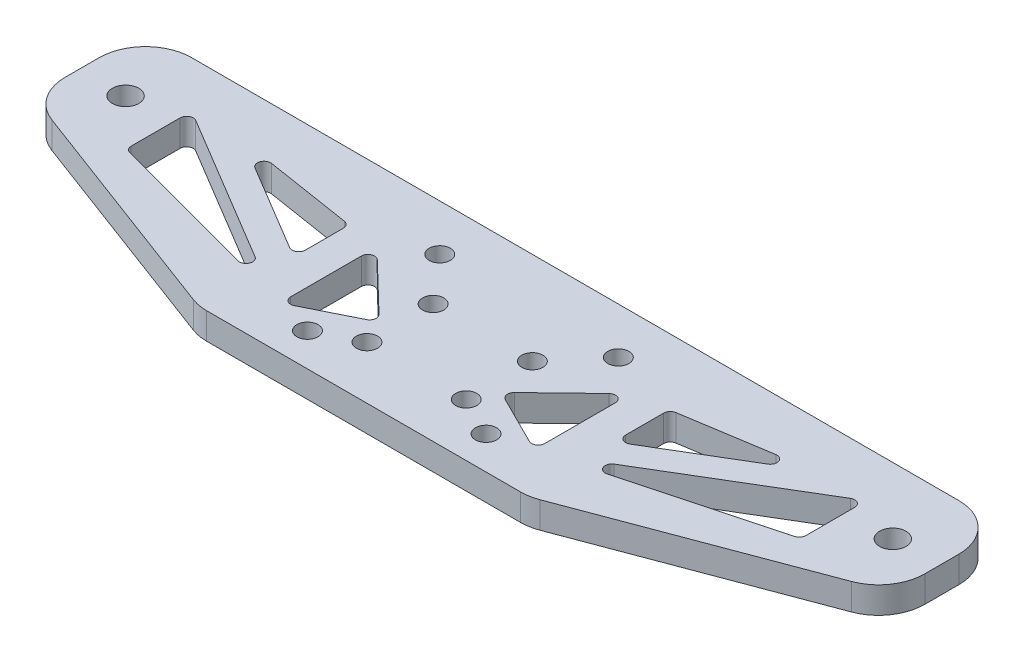
SolidWorks part; units mm, degrees
material "Thornel Mat VMA"
ref_plane "Front" through (0, 0, 0) normal (0, 0, 1) x (1, 0, 0)
ref_plane "Top" through (0, 0, 0) normal (0, 1, 0) x (1, 0, 0)
ref_plane "Right" through (0, 0, 0) normal (1, 0, 0) x (0, 0, -1)
sketch "草图1" plane through (0, 0, 0) normal (0, 1, 0) x (1, 0, 0)
  line L0 (0, 40.0348) -> (0, 0) construction
  line L1 (25, 0) -> (-25, 0)
  line L2 (-25, 0) -> (-65, 15)
  line L3 (-65, 15) -> (-65, 30)
  line L4 (-65, 30) -> (65, 30)
  line L5 (65, 15) -> (65, 30)
  line L6 (25, 0) -> (65, 15)
  point P9 (0, 30)
  dimension "D1" = 30
  dimension "D2" = 65
  dimension "D3" = 25
  dimension "D4" = 15
extrude "凸台-拉伸1" add sketch "草图1" along normal blind 4
sketch "草图2" plane through (0, 4, 0) normal (0, 1, 0) x (1, 0, 0)
  line L0 (0, 0) -> (0, 30) construction
  line L1 (65, 30) -> (-65, 30) construction
  line L2 (-7.5, 18) -> (-7.5, 8) construction
  line L3 (-7.5, 13) -> (7.5, 13) construction
  line L4 (7.5, 18) -> (7.5, 8) construction
  circle A0 centre (-7.5, 18) radius 1.6
  circle A3 centre (7.5, 18) radius 1.6
  circle A4 centre (-7.5, 8) radius 1.6
  circle A5 centre (7.5, 8) radius 1.6
  point P14 (0, 13)
  dimension "D1" = 3.2
  dimension "D2" = 10
  dimension "D3" = 7.5
  dimension "D4" = 17
extrude "切除-拉伸1" cut sketch "草图2" against normal through all
sketch "草图3" plane through (0, 4, 0) normal (0, 1, 0) x (1, 0, 0)
  line L0 (-65, 30) -> (-65, 15) construction
  line L1 (65, 30) -> (-65, 30) construction
  line L23 (-25, 0) -> (25, 0) construction
  line L24 (-51, 23.236) -> (-51, 15.8571)
  line L25 (-50.259, 14.8913) -> (-27.9213, 8.9003)
  line L26 (-27.1487, 10.7242) -> (-49.4864, 24.0941)
  line L27 (-38.7825, 22.3492) -> (-25.725, 14.5338)
  line L28 (-24.2114, 15.3918) -> (-24.2114, 21.1455)
  line L29 (-25.0554, 22.1333) -> (-38.113, 24.195)
  line L32 (-10.2291, 12.546) -> (-17.5171, 19.5762)
  line L33 (-65, 15) -> (-25, 0) construction
  line L34 (-13.5, 25) -> (-13.5, 5) construction
  line L35 (-19.2114, 18.8565) -> (-19.2114, 8.1823)
  line L36 (-17.7642, 7.2879) -> (-10.4762, 10.9319)
  line L37 (-13.5, 25) -> (-7.5, 18) construction
  line L38 (-7.5, 11.5643) -> (-9.2114, 11.5643) construction
  line L39 (0, 30) -> (0, 0) construction
  line L40 (7.5, 11.5643) -> (9.2114, 11.5643) construction
  line L41 (7.5, 20.5) -> (7.5, 10.5) construction
  line L42 (17.7642, 7.2879) -> (10.4762, 10.9319)
  line L43 (19.2114, 18.8565) -> (19.2114, 8.1823)
  line L44 (10.2291, 12.546) -> (17.5171, 19.5762)
  line L45 (25.0554, 22.1333) -> (38.113, 24.195)
  line L46 (24.2114, 15.3918) -> (24.2114, 21.1455)
  line L47 (38.7825, 22.3492) -> (25.725, 14.5338)
  line L48 (27.1487, 10.7242) -> (49.4864, 24.0941)
  line L49 (50.259, 14.8913) -> (27.9213, 8.9003)
  line L50 (51, 23.236) -> (51, 15.8571)
  line L51 (-7.5, 8) -> (-13.5, 5) construction
  circle A0 centre (-58, 22) radius 2
  arc A1 (-10.4762, 10.9319) -> (-10.2291, 12.546) centre (-10.9234, 11.8263) ccw
  arc A2 (-19.2114, 8.1823) -> (-17.7642, 7.2879) centre (-18.2114, 8.1823) ccw
  arc A3 (-19.2114, 18.8565) -> (-17.5171, 19.5762) centre (-18.2114, 18.8565) cw
  arc A4 (-24.2114, 21.1455) -> (-25.0554, 22.1333) centre (-25.2114, 21.1455) ccw
  arc A5 (-38.7825, 22.3492) -> (-38.113, 24.195) centre (-38.269, 23.2072) cw
  arc A6 (-25.725, 14.5338) -> (-24.2114, 15.3918) centre (-25.2114, 15.3918) ccw
  arc A7 (-27.1487, 10.7242) -> (-27.9213, 8.9003) centre (-27.6623, 9.8662) cw
  arc A8 (-51, 15.8571) -> (-50.259, 14.8913) centre (-50, 15.8571) ccw
  arc A9 (-51, 23.236) -> (-49.4864, 24.0941) centre (-50, 23.236) cw
  arc A10 (51, 23.236) -> (49.4864, 24.0941) centre (50, 23.236) ccw
  arc A11 (51, 15.8571) -> (50.259, 14.8913) centre (50, 15.8571) cw
  arc A12 (27.1487, 10.7242) -> (27.9213, 8.9003) centre (27.6623, 9.8662) ccw
  arc A13 (25.725, 14.5338) -> (24.2114, 15.3918) centre (25.2114, 15.3918) cw
  arc A14 (38.7825, 22.3492) -> (38.113, 24.195) centre (38.269, 23.2072) ccw
  arc A15 (24.2114, 21.1455) -> (25.0554, 22.1333) centre (25.2114, 21.1455) cw
  arc A16 (19.2114, 18.8565) -> (17.5171, 19.5762) centre (18.2114, 18.8565) ccw
  arc A17 (19.2114, 8.1823) -> (17.7642, 7.2879) centre (18.2114, 8.1823) cw
  arc A18 (10.4762, 10.9319) -> (10.2291, 12.546) centre (10.9234, 11.8263) cw
  circle A19 centre (58, 22) radius 2
  circle A20 centre (-13.5, 5) radius 1.6
  circle A21 centre (-13.5, 25) radius 1.6
  circle A22 centre (13.5, 5) radius 1.6
  circle A23 centre (13.5, 25) radius 1.6
  point P24 (-19.2114, 6.5643)
  point P32 (-19.2114, 21.2105)
  point P35 (-24.2114, 22)
  point P38 (-43.2114, 25)
  point P43 (-21, 7.044)
  point P46 (-51, 15.09)
  point P49 (-51, 25)
  point P86 (51, 25)
  point P87 (51, 15.09)
  point P88 (21, 7.044)
  point P89 (43.2114, 25)
  point P90 (24.2114, 22)
  point P91 (19.2114, 21.2105)
  point P92 (19.2114, 6.5643)
  dimension "D1" = 4
  dimension "D2" = 7
  dimension "D3" = 8
  dimension "D15" = 1
  dimension "D16" = 3.2
  dimension "D17" = 27
  dimension "D18" = 5
  dimension "D20" = 3.2
  dimension "D4" = 7
  dimension "D5" = 5
  dimension "D6" = 5
  dimension "D7" = 8
  dimension "D8" = 4
  dimension "D9" = 5
  dimension "D10" = 8
  dimension "D11" = 4
  dimension "D12" = 5
  dimension "D13" = 19
  dimension "D14" = 10
  dimension "D19" = 20
extrude "切除-拉伸2" cut sketch "草图3" against normal through all
sketch "草图4" plane through (0, 4, 0) normal (0, 1, 0) x (1, 0, 0)
  line L1 (-65, 30) -> (65, 30)
  line L2 (-65, 30) -> (-65, 32)
  line L3 (-65, 32) -> (65, 32)
  line L4 (65, 30) -> (65, 32)
  dimension "D1" = 2
extrude "凸台-拉伸2" add sketch "草图4" against normal blind 4
fillet "圆角1" radius 7 6 edges at (-25, 2, 0) (25, 2, 0) (65, 2, -15) (-65, 2, -15) (65, 2, -32) (-65, 2, -32)
